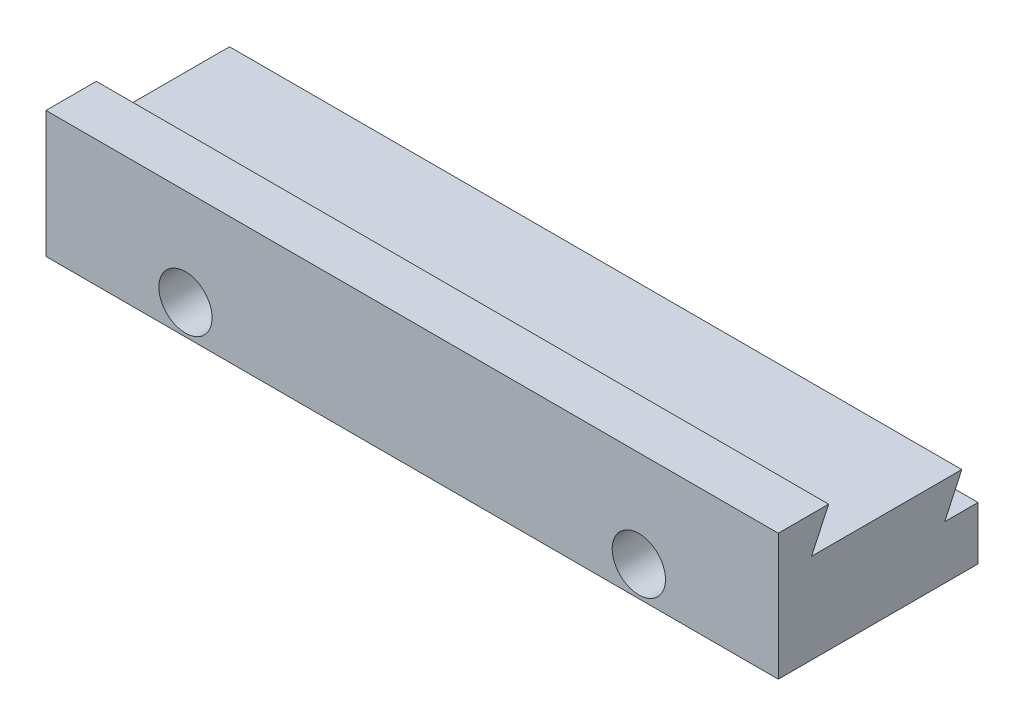
SolidWorks part; units mm, degrees
material "6061 Alloy"
ref_plane "Front Plane" through (0, 0, 0) normal (0, 0, 1) x (1, 0, 0)
ref_plane "Top Plane" through (0, 0, 0) normal (0, 1, 0) x (1, 0, 0)
ref_plane "Right Plane" through (0, 0, 0) normal (1, 0, 0) x (0, 0, -1)
sketch "Sketch1" plane through (0, 0, 0) normal (1, 0, 0) x (0, 0, -1)
  line L0 (0, 0) -> (0, 19)
  line L1 (0, 19) -> (7.5647, 19)
  line L2 (7.5647, 19) -> (5, 13.5)
  line L3 (5, 13.5) -> (27.5647, 13.5)
  line L4 (27.5647, 13.5) -> (25, 8)
  line L5 (25, 8) -> (30, 8)
  line L6 (30, 8) -> (30, 0)
  line L7 (30, 0) -> (0, 0)
  dimension "D1" = 65
  dimension "D2" = 65
  dimension "D3" = 5.5
  dimension "D4" = 5.5
  dimension "D5" = 8
  dimension "D6" = 5
  dimension "D7" = 25
  dimension "D8" = 5
extrude "Boss-Extrude1" add sketch "Sketch1" along normal blind 110
sketch "Sketch2" plane through (0, 0, -30) normal (0, 0, -1) x (-1, 0, 0)
  line L0 (-55, 8) -> (-55, 0) construction
  line L1 (-40.9488, 4.5) -> (-20.9488, 4.5) construction
  line L2 (-110, 8) -> (0, 8) construction
  line L3 (-110, 0) -> (0, 0) construction
  circle A0 centre (-20.9488, 4.5) radius 2.1
  circle A1 centre (-89.0512, 4.5) radius 2.1
  dimension "D2" = 4.2
  dimension "D1" = 20
  dimension "D3" = 3.5
extrude "Cut-Extrude1" cut sketch "Sketch2" against normal up to surface (30 mm away) up to face at (55, 9.5, 0)
sketch "Sketch3" plane through (0, 0, 0) normal (0, 0, 1) x (1, 0, 0)
  circle A0 centre (20.9488, 4.5) radius 4
  circle A1 centre (89.0512, 4.5) radius 4
  dimension "D1" = 8
extrude "Cut-Extrude2" cut sketch "Sketch3" against normal offset from surface (20 mm away) 10 up to face at (18.8488, 4.5, -30)
